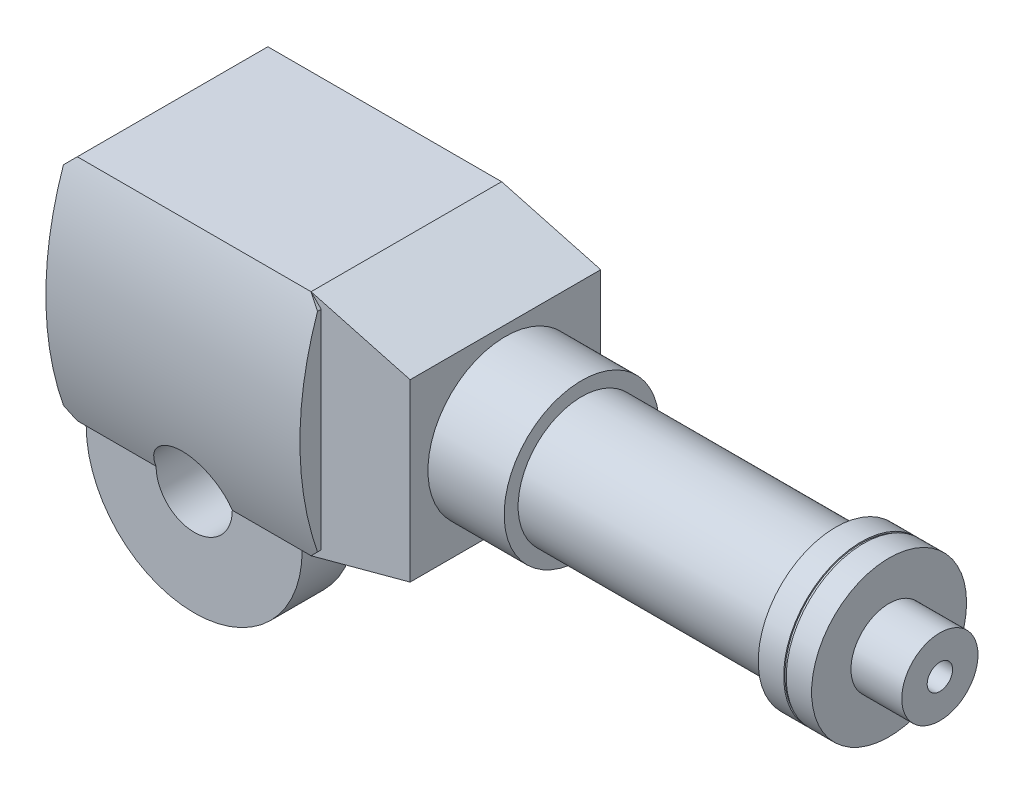
SolidWorks part; units mm, degrees
ref_plane "Front Plane" through (0, 0, 0) normal (0, 0, 1) x (1, 0, 0)
ref_plane "Top Plane" through (0, 0, 0) normal (0, 1, 0) x (1, 0, 0)
ref_plane "Right Plane" through (0, 0, 0) normal (1, 0, 0) x (0, 0, -1)
sketch "Sketch2" plane through (0, 0, 0) normal (0, 0, 1) x (1, 0, 0)
  line L1 (-25, 22.5) -> (25, 22.5)
  line L2 (-25, 22.5) -> (-25, -22.5)
  line L3 (-25, -22.5) -> (25, -22.5)
  line L4 (25, 22.5) -> (25, -22.5)
  line L5 (-25, 22.5) -> (25, -22.5) construction
  line L6 (-25, -22.5) -> (25, 22.5) construction
  point P0 (0, 0)
  dimension "D1" = 45
  dimension "D2" = 50
extrude "Boss-Extrude1" add sketch "Sketch2" against normal blind 37.5
sketch "Sketch3" plane through (25, 0, 0) normal (1, 0, 0) x (0, 0, -1)
  line L0 (0, 22.5) -> (0, -22.5)
  line L1 (18.75, 22.5) -> (18.75, -22.5) construction
  line L2 (37.5, 22.5) -> (0, 22.5) construction
  line L3 (37.5, -22.5) -> (0, -22.5) construction
  line L4 (37.5, 22.5) -> (37.5, -22.5)
  arc A0 (0, 22.5) -> (0, -22.5) centre (58.3095, 0) ccw
  arc A1 (37.5, 22.5) -> (37.5, -22.5) centre (-20.8095, 0) cw
  dimension "D1" = 62.5
extrude "Boss-Extrude2" add sketch "Sketch3" against normal through all
chamfer "Chamfer2" distance 2 angle 45 4 edges at (-25, 22.5, -18.75) (-25, -22.5, -18.75) (25, -22.5, -18.75) (25, 22.5, -18.75)
sketch "Sketch7" plane through (0, 0, 0) normal (0, 0, 1) x (1, 0, 0)
  line L0 (-23, -22.5) -> (23, -22.5) construction
  line L1 (-21.25, -22.5) -> (21.25, -22.5)
  arc A0 (-21.25, -22.5) -> (21.25, -22.5) centre (0, -22.5) ccw
extrude "Boss-Extrude3" add sketch "Sketch7" against normal blind 10.5
sketch "Sketch8" plane through (0, 0, -10.5) normal (0, 0, -1) x (-1, 0, 0)
  line L0 (-10, -22.5) -> (10, -22.5)
  line L1 (-21.25, -22.5) -> (21.25, -22.5) construction
  line L2 (10, -22.5) -> (10, -37.5)
  line L4 (23, -22.5) -> (-23, -22.5) construction
  line L5 (-10, -22.5) -> (-10, -37.5)
  arc A0 (-10, -37.5) -> (10, -37.5) centre (0, -22.5) ccw
  circle A1 centre (0, -22.5) radius 2.5
  dimension "D1" = 5
extrude "Boss-Extrude4" add sketch "Sketch8" along normal blind 25 contours A0 L2 L0 L5
sketch "Sketch10" plane through (0, 0, -35.5) normal (0, 0, -1) x (-1, 0, 0)
  line L0 (-10, -22.5) -> (10, -22.5) construction
  circle A0 centre (0, -22.5) radius 2.5
  dimension "D1" = 5
extrude "Cut-Extrude2" cut sketch "Sketch10" against normal through all both and the other way through all
sketch "Sketch13" plane through (0, 0, 0) normal (0, 0, 1) x (1, 0, 0)
  line L0 (23, 22.5) -> (23, -22.5)
  line L2 (42.5, 0) -> (42.5, 17.25)
  line L3 (42.5, 0) -> (42.5, -17.25)
  line L4 (23, 22.5) -> (42.5, 17.25)
  line L5 (42.5, -17.25) -> (23, -22.5)
extrude "Boss-Extrude6" add sketch "Sketch13" against normal blind 37.5
sketch "Sketch15" plane through (42.5, 0, 0) normal (1, 0, 0) x (0, 0, -1)
  line L0 (0, 0) -> (37.5, 0) construction
  line L1 (37.5, -17.25) -> (37.5, 17.25) construction
  circle A0 centre (18.75, 0) radius 15.25
  dimension "D1" = 30.5
extrude "Boss-Extrude8" add sketch "Sketch15" along normal blind 15
sketch "Sketch16" plane through (57.5, 0, 0) normal (1, 0, 0) x (0, 0, -1)
  circle A0 centre (18.75, 0) radius 12.5
  dimension "D1" = 25
extrude "Boss-Extrude9" add sketch "Sketch16" along normal blind 50
sketch "Sketch17" plane through (107.5, 0, 0) normal (1, 0, 0) x (0, 0, -1)
  circle A0 centre (18.75, 0) radius 15.25
  dimension "D1" = 30.5
extrude "Boss-Extrude10" add sketch "Sketch17" along normal blind 5
sketch "Sketch18" plane through (112.5, 0, 0) normal (1, 0, 0) x (0, 0, -1)
  circle A0 centre (18.75, 0) radius 15
  dimension "D1" = 30
extrude "Boss-Extrude11" add sketch "Sketch18" along normal blind 0.5
sketch "Sketch19" plane through (113, 0, 0) normal (1, 0, 0) x (0, 0, -1)
  circle A0 centre (18.75, 0) radius 15.25
extrude "Boss-Extrude12" add sketch "Sketch19" along normal blind 5
sketch "Sketch20" plane through (118, 0, 0) normal (1, 0, 0) x (0, 0, -1)
  circle A0 centre (18.75, 0) radius 7.5
  circle A1 centre (18.75, 0) radius 2.5
  dimension "D1" = 15
  dimension "D2" = 5
extrude "Boss-Extrude13" add sketch "Sketch20" along normal blind 10
sketch "Sketch21" plane through (0, 0, 0) normal (0, 0, 1) x (1, 0, 0)
  circle A0 centre (0, -22.5) radius 7.5
  dimension "D1" = 15
extrude "Cut-Extrude3" cut sketch "Sketch21" against normal blind 10 and the other way through all
